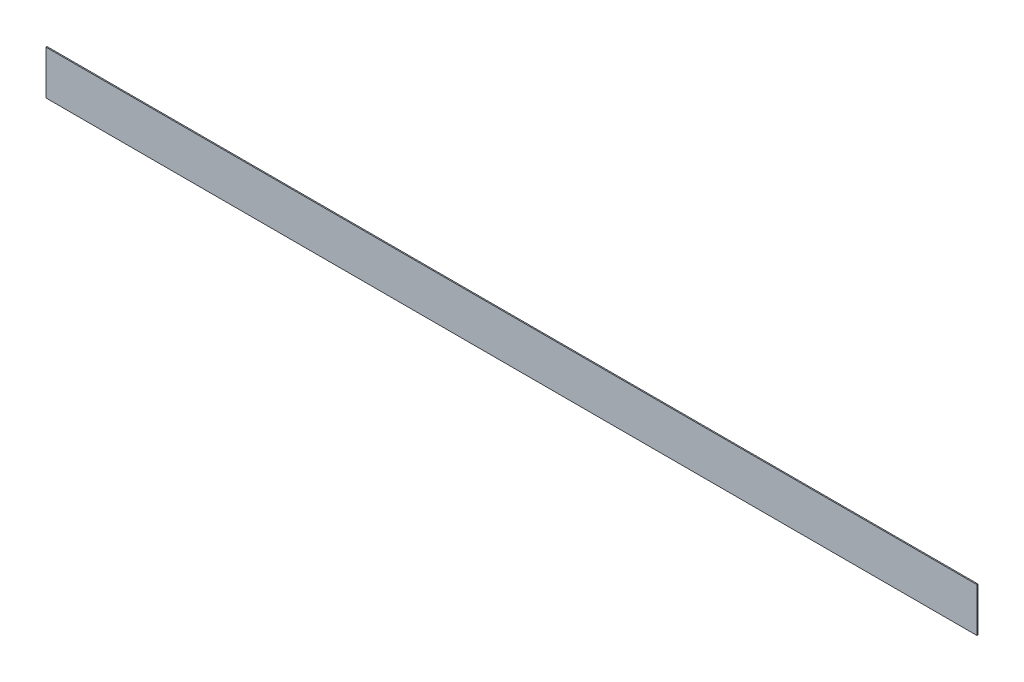
SolidWorks part; units mm, degrees
ref_plane "Front Plane" through (0, 0, 0) normal (0, 0, 1) x (1, 0, 0)
ref_plane "Top Plane" through (0, 0, 0) normal (0, 1, 0) x (1, 0, 0)
ref_plane "Right Plane" through (0, 0, 0) normal (1, 0, 0) x (0, 0, -1)
other "Configuration Table"
sketch "Sketch1" plane through (0, 0, 0) normal (0, 0, 1) x (1, 0, 0)
  line L1 (66, 1610) -> (1334, 1610)
  line L2 (66, 1610) -> (66, 1670)
  line L3 (66, 1670) -> (1334, 1670)
  line L4 (1334, 1610) -> (1334, 1670)
extrude "STORE_panel_bant_ust_1" add sketch "Sketch1" along normal blind 1.5 from offset 38.5 separate body
